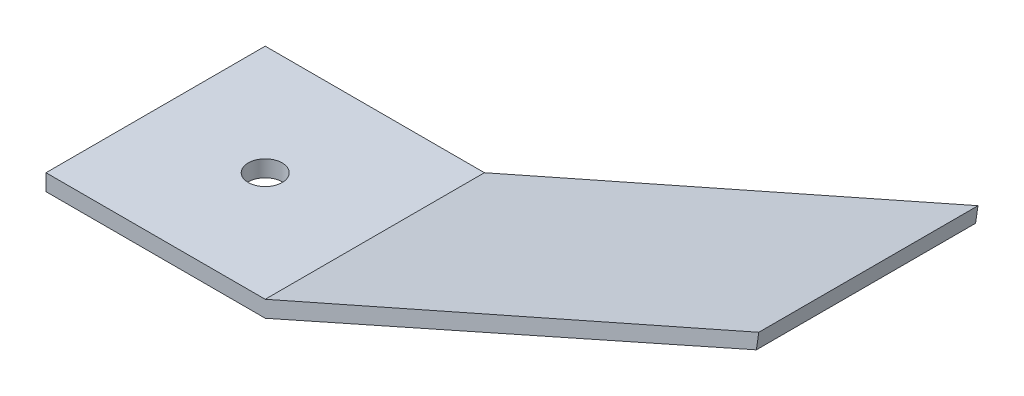
SolidWorks part; units mm, degrees
ref_plane "Front Plane" through (0, 0, 0) normal (0, 0, 1) x (1, 0, 0)
ref_plane "Top Plane" through (0, 0, 0) normal (0, 1, 0) x (1, 0, 0)
ref_plane "Right Plane" through (0, 0, 0) normal (1, 0, 0) x (0, 0, -1)
sketch "Sketch1" plane through (0, 0, 0) normal (0, 1, 0) x (1, 0, 0)
  line L1 (-20, 20) -> (20, 20)
  line L2 (-20, 20) -> (-20, -20)
  line L3 (-20, -20) -> (20, -20)
  line L4 (20, 20) -> (20, -20)
  line L5 (-20, 20) -> (20, -20) construction
  line L6 (-20, -20) -> (20, 20) construction
  circle A0 centre (0, 0) radius 3.1
  point P0 (0, 0)
  dimension "D3" = 6.2
  dimension "D1" = 40
  dimension "D2" = 40
extrude "Boss-Extrude1" add sketch "Sketch1" along normal blind 3
sketch "Sketch3" plane through (20, 0, 0) normal (1, 0, 0) x (0, 0, -1)
  line L0 (325.8815, -133.4366) -> (-192.7, 3.825) construction
  line L1 (325.8815, -133.4366) -> (-192.7, 3.825) construction
  line L2 (707.1168, 178.8881) -> (-192.7, 3.825) construction
  line L3 (707.1168, 178.8881) -> (-192.7, 3.825) construction
  line L4 (709.5421, 166.4219) -> (704.6914, 191.3544) construction
  line L5 (709.5421, 166.4219) -> (-190.2746, -8.6413) construction
  line L6 (-190.2746, -8.6413) -> (-195.1254, 16.2913) construction
  line L7 (-195.1254, 16.2913) -> (704.6914, 191.3544) construction
  line L8 (-20, 0) -> (-20, 62.4151) construction
  line L9 (-20, 62.4151) -> (20, 62.4151) construction
  line L10 (20, 62.4151) -> (20, 0) construction
  line L11 (20, 0) -> (-20, 0) construction
  line L12 (20, 42.8156) -> (-20, 42.8156)
  line L13 (-20, 42.8156) -> (-20, 39.8156)
  line L14 (-20, 39.8156) -> (20, 39.8156)
  line L15 (20, 39.8156) -> (20, 42.8156)
  line L16 (-20, 3) -> (-20, 0) construction
  line L17 (0, 39.8156) -> (0, 42.8156) construction
  point P6 (707.1168, 178.8881)
  point P20 (0, 41.3156)
  dimension "D1" = 90
  dimension "D2" = 25.4
sketch "Sketch4" plane through (0, 0, -20) normal (0, 0, -1) x (-1, 0, 0)
  line L1 (-130, 178.8881) -> (-104.345, 3.825)
  point P2 (-20, 42.8156)
  point P3 (-20, 39.8156)
sketch "Sketch6" plane through (0, 0, -20) normal (0, 0, -1) x (-1, 0, 0)
  line L0 (-20, 42.8156) -> (-110.059, 42.8156) construction
  line L1 (-130, 178.8881) -> (-104.345, 3.825) construction
  line L2 (-20, 39.8156) -> (-109.6193, 39.8156) construction
  line L3 (-109.6193, 39.8156) -> (-20, 0)
  line L4 (-20, -8.6413) -> (-20, 16.2913) construction
  line L5 (-20, 0) -> (-20, 3)
  line L6 (-20, 3) -> (-110.059, 42.8156)
  line L7 (-110.059, 42.8156) -> (-109.6193, 39.8156)
extrude "Boss-Extrude2" add sketch "Sketch6" against normal up to surface (40 mm away) up to face at (0, 1.5, 20)
